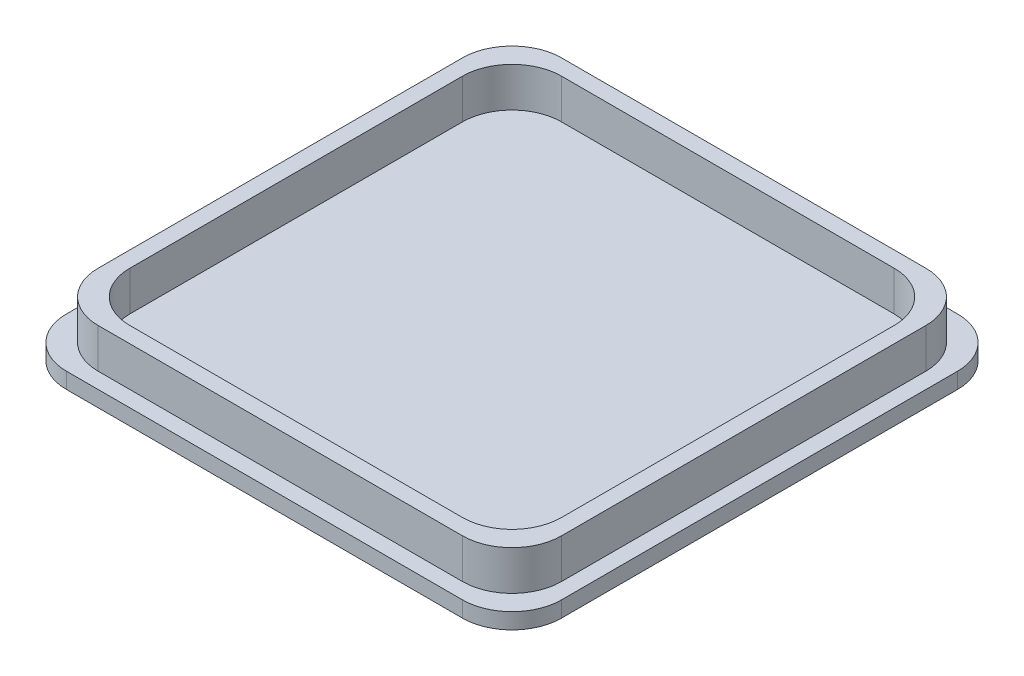
SolidWorks part; units mm, degrees
ref_plane "Спереди" through (0, 0, 0) normal (0, 0, 1) x (1, 0, 0)
ref_plane "Сверху" through (0, 0, 0) normal (0, 1, 0) x (1, 0, 0)
ref_plane "Справа" through (0, 0, 0) normal (1, 0, 0) x (0, 0, -1)
sketch "Sketch1" plane through (0, 0, 0) normal (0, 1, 0) x (1, 0, 0)
  line L1 (-25, -25) -> (25, -25)
  line L2 (-25, -25) -> (-25, 25)
  line L3 (-25, 25) -> (25, 25)
  line L4 (25, -25) -> (25, 25)
  line L5 (-25, -25) -> (25, 25) construction
  line L6 (-25, 25) -> (25, -25) construction
  point P0 (0, 0)
  dimension "D1" = 50
  dimension "D2" = 50
extrude "Boss-Extrude1" add sketch "Sketch1" along normal blind 1.6
sketch "Sketch2" plane through (0, 1.6, 0) normal (0, 1, 0) x (1, 0, 0)
  line L4 (21.8, -21.8) -> (21.8, 21.8)
  line L5 (21.8, 21.8) -> (-21.8, 21.8)
  line L6 (-21.8, 21.8) -> (-21.8, -21.8)
  line L7 (-21.8, -21.8) -> (21.8, -21.8)
  line L8 (23.4, -23.4) -> (23.4, 23.4)
  line L9 (23.4, 23.4) -> (-23.4, 23.4)
  line L10 (-23.4, 23.4) -> (-23.4, -23.4)
  line L11 (-23.4, -23.4) -> (23.4, -23.4)
  line L12 (23.4, -23.4) -> (23.4, 23.4)
  line L13 (23.4, 23.4) -> (-23.4, 23.4)
  line L14 (-23.4, 23.4) -> (-23.4, -23.4)
  line L15 (-23.4, -23.4) -> (23.4, -23.4)
  dimension "D1" = 1.6
  dimension "D2" = 1.6
extrude "Boss-Extrude2" add sketch "Sketch2" along normal blind 4
fillet "Fillet1" radius 5 12 edges at (-21.8, 3.6, 21.8) (21.8, 3.6, 21.8) (21.8, 3.6, -21.8) (-23.4, 3.6, -23.4) (-25, 0.8, 25) (25, 0.8, 25) (25, 0.8, -25) (23.4, 3.6, -23.4) (-23.4, 3.6, 23.4) (23.4, 3.6, 23.4) (-21.8, 3.6, -21.8) (-25, 0.8, -25)
